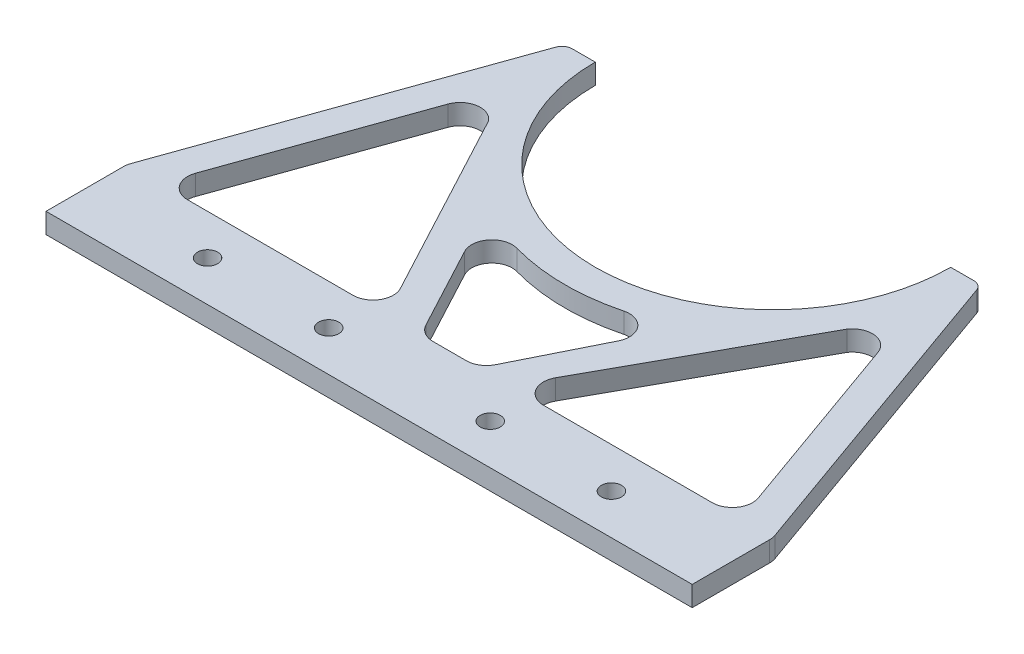
SolidWorks part; units mm, degrees
ref_plane "Front Plane" through (0, 0, 0) normal (0, 0, 1) x (1, 0, 0)
ref_plane "Top Plane" through (0, 0, 0) normal (0, 1, 0) x (1, 0, 0)
ref_plane "Right Plane" through (0, 0, 0) normal (1, 0, 0) x (0, 0, -1)
sketch "Sketch1" plane through (0, 0, 0) normal (0, 1, 0) x (1, 0, 0)
  line L0 (-55.88, 63.5) -> (-65.405, 63.5)
  line L1 (-101.6, 63.5) -> (-55.88, 63.5) construction
  line L2 (-101.6, 63.5) -> (-101.6, -63.5) construction
  line L3 (-101.6, -63.5) -> (101.6, -63.5)
  line L4 (101.6, 63.5) -> (101.6, -63.5) construction
  line L5 (55.88, 63.5) -> (65.405, 63.5)
  line L6 (-65.405, 63.5) -> (-101.2318, -37.0663)
  line L7 (0, 119.38) -> (0, 50000) construction
  line L8 (55.88, 63.5) -> (101.6, 63.5) construction
  line L9 (-101.6, -39.1973) -> (-101.6, -63.5)
  line L10 (101.6, -63.5) -> (101.6, -39.1973)
  line L11 (101.2318, -37.0663) -> (65.405, 63.5)
  line L12 (-82.4855, -38.1) -> (-30.4925, -38.1)
  line L13 (-67.621, 28.897) -> (-88.4673, -29.619)
  line L14 (88.4673, -29.619) -> (67.621, 28.897)
  line L15 (-56.4324, 60.3035) -> (-92.6274, -41.2965) construction
  line L16 (92.6274, -41.2965) -> (56.4324, 60.3035) construction
  line L17 (-24.8906, -28.7596) -> (-57.6986, 32.6993)
  line L18 (0, 22.8283) -> (0, -93.9069) construction
  line L19 (-10.9009, -34.7404) -> (-24.8462, -8.6166)
  line L20 (-11.2649, -34.0585) -> (-49.2959, 37.1849) construction
  line L21 (10.8591, -34.5773) -> (23.6826, -8.7888)
  line L22 (23.8626, -28.6846) -> (57.6986, 32.6993)
  line L23 (-19.6676, -38.544) -> (-57.6986, 32.6993) construction
  line L24 (-5.299, -38.1) -> (5.1732, -38.1)
  line L25 (29.4237, -38.1) -> (82.4855, -38.1)
  line L26 (-65.405, 63.5) -> (-101.6, -38.1) construction
  line L27 (101.6, -38.1) -> (65.405, 63.5) construction
  arc A0 (-55.88, 63.5) -> (55.88, 63.5) centre (0, 63.5) ccw
  circle A1 centre (-63.5, -50.8) radius 3.175
  circle A2 centre (63.5, -50.8) radius 3.175
  arc A3 (-17.5414, 0.4912) -> (16.4041, 0.1855) centre (0, 63.5) ccw
  arc A4 (-65.405, 63.5) -> (65.405, 63.5) centre (0, 63.5) ccw construction
  arc A5 (-56.1844, 30.0168) -> (-67.621, 28.897) centre (-61.6392, 26.766) ccw
  arc A6 (-24.8906, -28.7596) -> (-30.4925, -38.1) centre (-30.4925, -31.75) cw
  arc A7 (-82.4855, -38.1) -> (-88.4673, -29.619) centre (-82.4855, -31.75) cw
  arc A8 (-17.5414, 0.4912) -> (-24.8462, -8.6166) centre (-19.2444, -5.6262) ccw
  arc A9 (16.4041, 0.1855) -> (23.6826, -8.7888) centre (17.9967, -5.9615) cw
  arc A10 (-10.9009, -34.7404) -> (-5.299, -38.1) centre (-5.299, -31.75) ccw
  arc A11 (5.1732, -38.1) -> (10.8591, -34.5773) centre (5.1732, -31.75) ccw
  arc A12 (56.1844, 30.0168) -> (57.6986, 32.6993) centre (0, 63.5) cw construction
  arc A13 (56.1844, 30.0168) -> (67.621, 28.897) centre (61.6392, 26.766) cw
  arc A14 (23.8626, -28.6846) -> (29.4237, -38.1) centre (29.4237, -31.75) ccw
  arc A15 (82.4855, -38.1) -> (88.4673, -29.619) centre (82.4855, -31.75) ccw
  arc A16 (-57.6986, 32.6993) -> (-56.1844, 30.0168) centre (0, 63.5) cw construction
  arc A17 (16.4041, 0.1855) -> (-17.5414, 0.4912) centre (0, 63.5) cw
  arc A18 (-101.6, -39.1973) -> (-101.2318, -37.0663) centre (-95.25, -39.1973) cw
  arc A19 (101.6, -39.1973) -> (101.2318, -37.0663) centre (95.25, -39.1973) ccw
  circle A20 centre (-25.4, -50.8) radius 3.175
  circle A21 centre (25.4, -50.8) radius 3.175
  point P0 (0, 0)
  point P40 (-9.1074, -38.1)
  point P57 (9.1074, -38.1)
  point P64 (91.4886, -38.1)
  point P75 (0, 0)
  dimension "D3" = 6.35
  dimension "D6" = 6.35
  dimension "D9" = 9.525
  dimension "D15" = 6.35
  dimension "D16" = 6.35
  dimension "D17" = 6.35
  dimension "D14" = 6.35
  dimension "D18" = 6.35
  dimension "D19" = 6.35
  dimension "D20" = 6.35
  dimension "D21" = 6.35
  dimension "D22" = 6.35
  dimension "D23" = 6.35
  dimension "D24" = 6.35
  dimension "D1" = 127
  dimension "D2" = 203.2
  dimension "D4" = 12.7
  dimension "D5" = 38.1
  dimension "D7" = 12.7
  dimension "D8" = 38.1
  dimension "D10" = 25.4
  dimension "D25" = 76.2
  dimension "D26" = 76.2
  dimension "D11" = 9.525
  dimension "D12" = 9.525
  dimension "D13" = 9.525
extrude "Boss-Extrude1" add sketch "Sketch1" along normal blind 6.35
fillet "Fillet1" radius 3.175 2 edges at (65.405, 3.175, -63.5) (-65.405, 3.175, -63.5)
